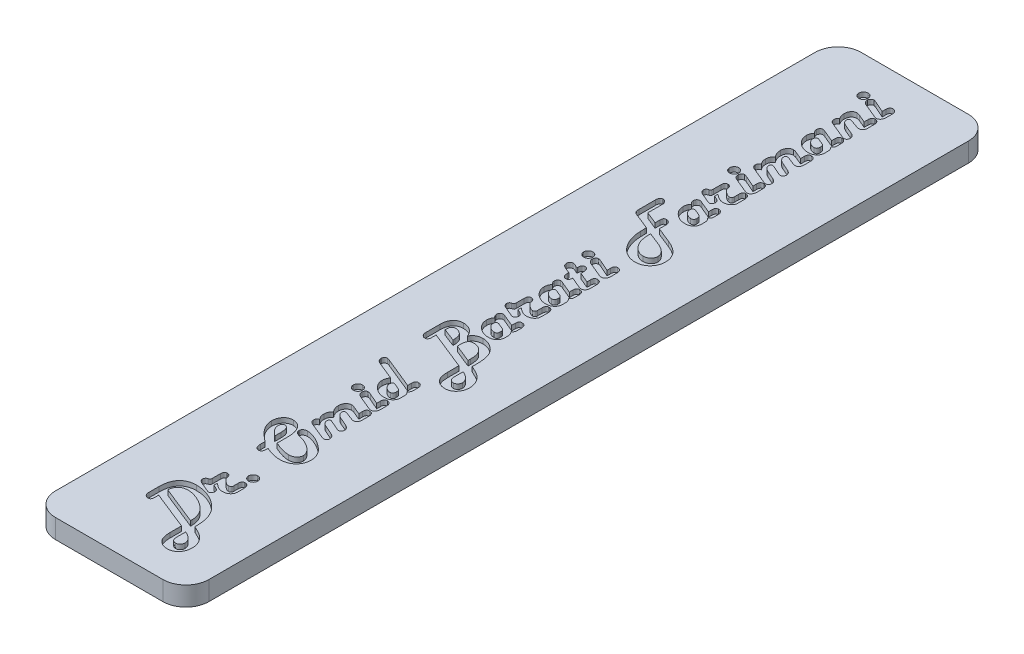
SolidWorks part; units mm, degrees
ref_plane "Front Plane" through (0, 0, 0) normal (0, 0, 1) x (1, 0, 0)
ref_plane "Top Plane" through (0, 0, 0) normal (0, 1, 0) x (1, 0, 0)
ref_plane "Right Plane" through (0, 0, 0) normal (1, 0, 0) x (0, 0, -1)
sketch "Sketch1" plane through (0, 0, 0) normal (0, 0, 1) x (1, 0, 0)
  line L0 (0, 1.5875) -> (0, -1.5875)
  line L1 (-12.7, 0) -> (12.7, 0) construction
  point P6 (0, 0)
  dimension "Width" = 25.4
  dimension "Thk" = 3.175
sketch "Sketch2" plane through (0, 0, 0) normal (1, 0, 0) x (0, 0, -1)
  line L0 (66.675, 0) -> (-66.675, 0)
  point P4 (0, 0)
  dimension "Length" = 133.35
sketch "Sketch3" plane through (0, 0, 0) normal (0, 0, 1) x (1, 0, 0)
  line L1 (12.7, 1.5875) -> (-12.7, 1.5875)
  line L2 (12.7, 1.5875) -> (12.7, -1.5875)
  line L3 (12.7, -1.5875) -> (-12.7, -1.5875)
  line L4 (-12.7, 1.5875) -> (-12.7, -1.5875)
  line L5 (12.7, 1.5875) -> (-12.7, -1.5875) construction
  line L6 (12.7, -1.5875) -> (-12.7, 1.5875) construction
  point P0 (0, 0)
extrude "Boss-Extrude1" add sketch "Sketch3" along normal up to vertex (66.675 mm away) and the other way up to vertex (66.675 mm away) up to point (0, 0, 66.675) other way up to point (0, 0, -66.675)
sketch "Sketch5" plane through (0, 1.5875, 0) normal (0, 1, 0) x (1, 0, 0)
  line L2 (9.652, -66.675) -> (-9.398, -66.675) construction
  line L3 (-12.7, -63.5025) -> (-12.7, 63.627) construction
  line L12 (12.7, -66.675) -> (12.7, 66.675)
  line L13 (12.7, 66.675) -> (-12.7, 66.675)
  line L14 (-12.7, 66.675) -> (-12.7, -66.675)
  line L15 (-12.7, -66.675) -> (12.7, -66.675)
  line L16 (12.7, -62.865) -> (12.7, 62.865)
  line L17 (8.89, 66.675) -> (-8.89, 66.675)
  line L18 (-12.7, 62.865) -> (-12.7, -62.865)
  line L19 (-8.89, -66.675) -> (8.89, -66.675)
  arc A8 (12.7, 62.865) -> (8.89, 66.675) centre (8.89, 62.865) ccw
  arc A9 (-8.89, 66.675) -> (-12.7, 62.865) centre (-8.89, 62.865) ccw
  arc A10 (12.7, -62.865) -> (8.89, -66.675) centre (8.89, -62.865) cw
  arc A11 (-8.89, -66.675) -> (-12.7, -62.865) centre (-8.89, -62.865) cw
  dimension "D2" = 3.81
  dimension "D1" = 0
extrude "Cut-Extrude2" cut sketch "Sketch5" against normal through all flip side to cut
sketch "Sketch4" plane through (0, 1.5875, 0) normal (0, 1, 0) x (1, 0, 0)
  line L0 (0, 0) -> (2.54, 0) construction
  line L1 (2.54, -66.675) -> (2.54, 66.675) construction
  line L2 (8.89, 66.675) -> (-8.89, 66.675) construction
  text T0 "Dr. Omid Barati Farimani" font "Harlow Solid Italic" height in points 24
  point P8 (2.54, 0)
  dimension "D1" = 2.54
extrude "Cut-Extrude1" cut sketch "Sketch4" against normal blind 0.7937
